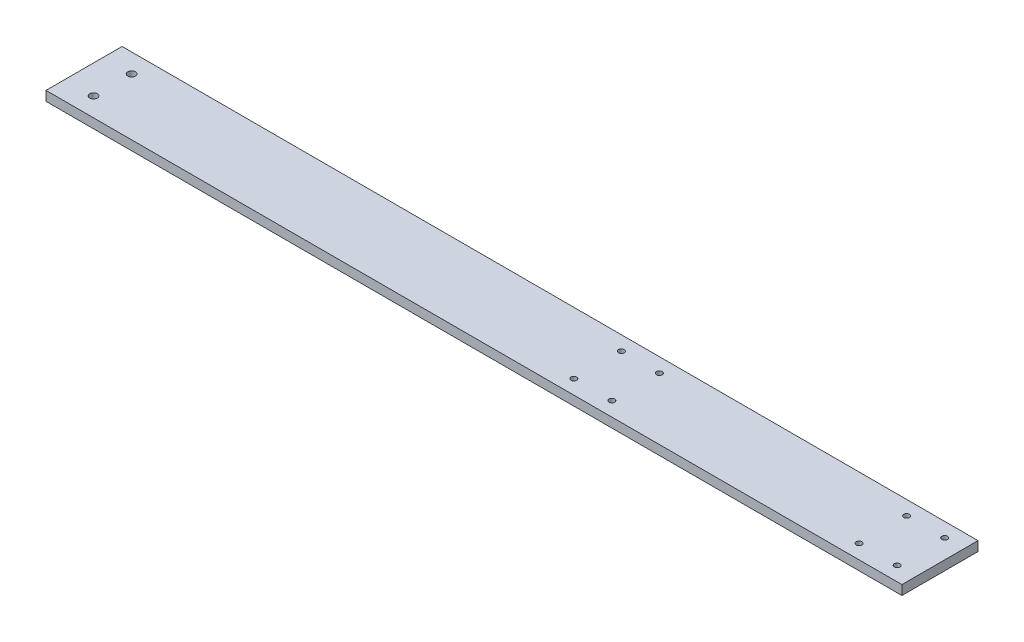
SolidWorks part; units mm, degrees
material "Thornel Mat VMA"
ref_plane "前视基准面" through (0, 0, 0) normal (0, 0, 1) x (1, 0, 0)
ref_plane "上视基准面" through (0, 0, 0) normal (0, 1, 0) x (1, 0, 0)
ref_plane "右视基准面" through (0, 0, 0) normal (1, 0, 0) x (0, 0, -1)
sketch "草图1" plane through (0, 0, 0) normal (0, 1, 0) x (1, 0, 0)
  line L0 (0, 0) -> (225, 0) construction
  line L1 (-225, 20) -> (225, 20)
  line L2 (-225, 20) -> (-225, -20)
  line L3 (-225, -20) -> (225, -20)
  line L4 (225, 20) -> (225, -20)
  line L5 (0, 0) -> (0, 20) construction
  circle A0 centre (215, 12.5) radius 1.5
  circle A1 centre (195, 12.5) radius 1.5
  circle A2 centre (195, -12.5) radius 1.5
  circle A3 centre (215, -12.5) radius 1.5
  circle A4 centre (65, -12.5) radius 1.5
  circle A5 centre (45, 12.5) radius 1.5
  circle A6 centre (65, 12.5) radius 1.5
  circle A7 centre (45, -12.5) radius 1.5
  circle A8 centre (-210, 10) radius 2
  circle A9 centre (-210, -10) radius 2
  point P4 (0, 20)
  point P6 (225, 0)
  point P28 (0, 0)
  dimension "D3" = 3
  dimension "D10" = 4
  dimension "D1" = 40
  dimension "D2" = 450
  dimension "D4" = 20
  dimension "D5" = 25
  dimension "D6" = 10
  dimension "D7" = 150
  dimension "D8" = 20
  dimension "D9" = 25
  dimension "D11" = 20
  dimension "D12" = 10
  dimension "D13" = 15
extrude "凸台-拉伸1" add sketch "草图1" along normal blind 5
chamfer "倒角1" distance 2 angle 45 8 edges at (45, 0, -11) (45, 0, 11) (65, 0, 11) (65, 0, -11) (215, 0, -11) (195, 0, -11) (195, 0, 11) (215, 0, 11)
